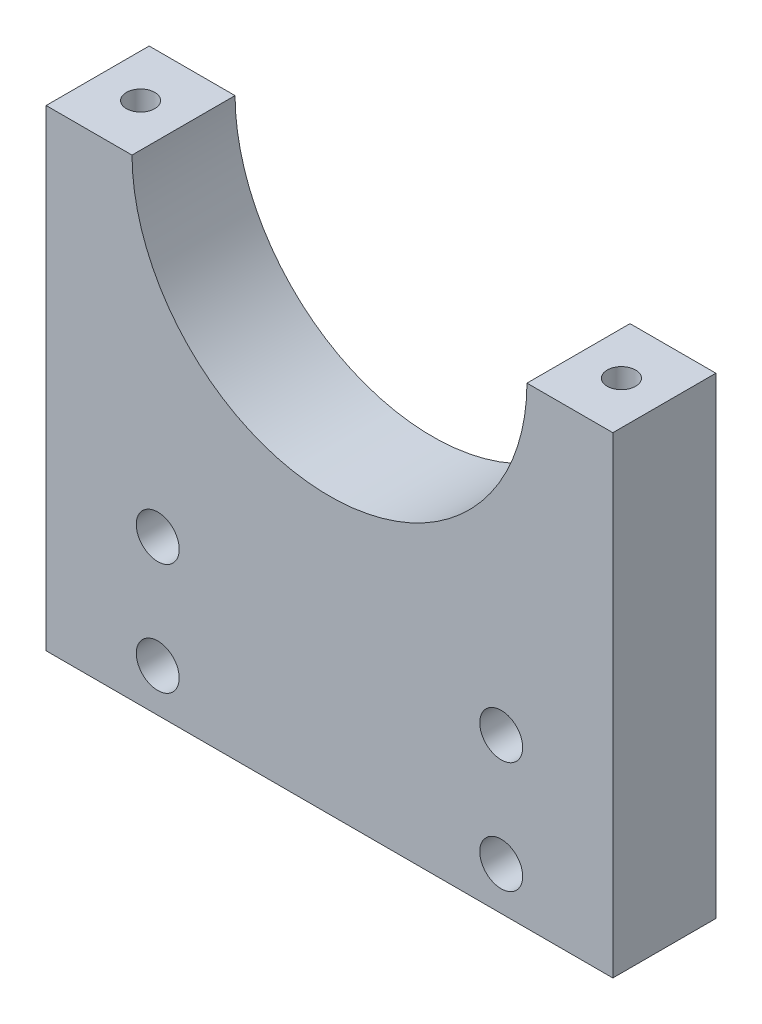
SolidWorks part; units mm, degrees
material "SKD11淬火HRC56-60"
ref_plane "前基準面" through (0, 0, 0) normal (0, 0, 1) x (1, 0, 0)
ref_plane "上基準面" through (0, 0, 0) normal (0, 1, 0) x (1, 0, 0)
ref_plane "右基準面" through (0, 0, 0) normal (1, 0, 0) x (0, 0, -1)
sketch "草图1" plane through (0, 0, 0) normal (0, 0, 1) x (1, 0, 0)
  line L1 (0, 0) -> (66, 0)
  line L2 (0, 0) -> (0, 55)
  line L3 (0, 55) -> (66, 55)
  line L4 (66, 0) -> (66, 55)
  dimension "D1" = 66
  dimension "D2" = 55
extrude "凸台-拉伸1" add sketch "草图1" along normal blind 12
sketch "草图2" plane through (0, 0, 12) normal (0, 0, 1) x (1, 0, 0)
  line L0 (33, 55) -> (33, 47.1725) construction
  line L1 (66, 55) -> (0, 55) construction
  circle A0 centre (33, 55.1) radius 23
  dimension "D2" = 46
  dimension "D1" = 0.1
extrude "切除-拉伸1" cut sketch "草图2" against normal through all
hole_wizard "M6 螺纹孔1" positions "草图4" profile "草图3" tap size "M6" standard "ISO" end condition through all
sketch "草图4" plane through (0, 0, 12) normal (0, 0, 1) x (1, 0, 0)
  line L0 (33, 0) -> (33, 35.1693) construction
  line L1 (0, 0) -> (66, 0) construction
  point P0 (13, 18)
  point P1 (53, 18)
  point P3 (13, 5)
  point P5 (53, 5)
  dimension "D1" = 40
  dimension "D2" = 5
  dimension "D3" = 13
sketch "草图3" plane through (13, 18, 12) normal (1, 0, 0) x (0, -1, 0)
  line L0 (0, 0) -> (0, 12)
  line L1 (0, 12) -> (2.5, 12)
  line L2 (2.5, 12) -> (2.5, 0)
  line L5 (2.5, 0) -> (0, 0)
  line L11 (0, -6.35) -> (0, 107.95) construction
  dimension "通孔螺纹孔钻头直径" = 5
  dimension "通孔螺纹孔钻头深度" = 12
cosmetic thread "孔螺蚊线1" parameters "D2"=6
cosmetic thread "孔螺蚊线2" parameters "D2"=6
cosmetic thread "孔螺蚊线3" parameters "D2"=6
cosmetic thread "孔螺蚊线4" parameters "D2"=6
hole_wizard "M4 螺纹孔1" positions "草图6" profile "草图5" tap size "M4" standard "ISO"
sketch "草图6" plane through (0, 55, 0) normal (0, 1, 0) x (-1, 0, 0)
  point P0 (-5, 6)
  point P1 (-61, 6)
sketch "草图5" plane through (5, 55, 6) normal (1, 0, 0) x (0, 0, 1)
  line L0 (0, 0) -> (0, 11.0914)
  line L1 (0, 11.0914) -> (1.65, 10.1)
  line L2 (1.65, 10.1) -> (1.65, 0)
  line L5 (1.65, 0) -> (0, 0)
  line L10 (0, 11.0914) -> (-1.65, 10.1) construction
  line L11 (0, -6.35) -> (0, 107.95) construction
  dimension "螺纹孔钻头直径" = 3.3
  dimension "螺纹孔钻头深度" = 10.1
  dimension "导头角度" = 118
cosmetic thread "孔螺蚊线5" parameters "D1"=8, "D2"=4
cosmetic thread "孔螺蚊线6" parameters "D1"=8, "D2"=4
